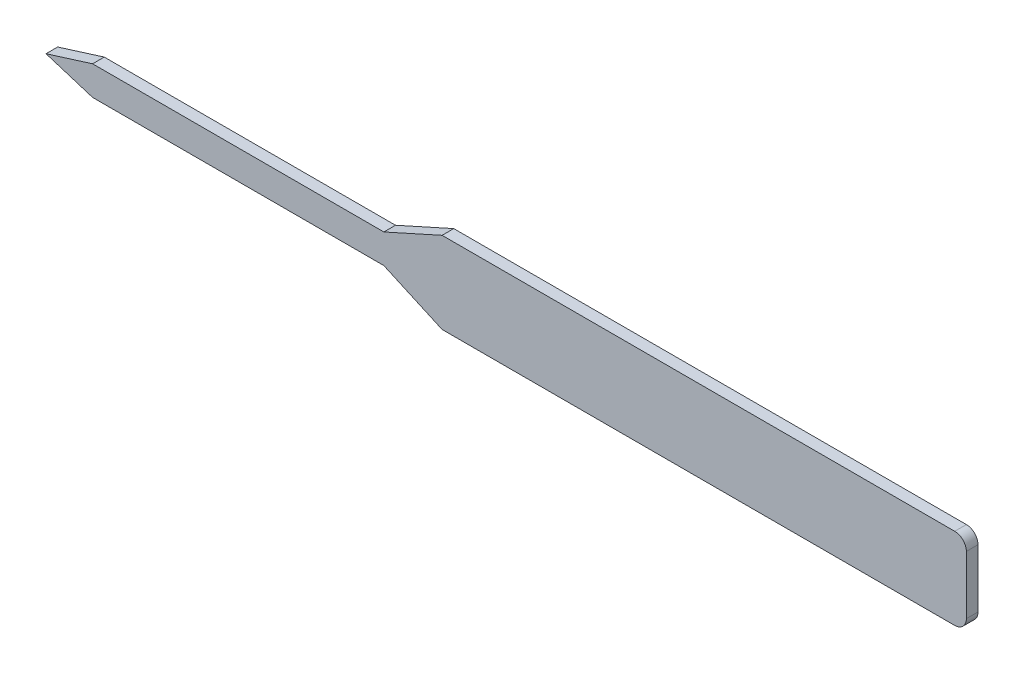
SolidWorks part; units mm, degrees
ref_plane "Front Plane" through (0, 0, 0) normal (0, 0, 1) x (1, 0, 0)
ref_plane "Top Plane" through (0, 0, 0) normal (0, 1, 0) x (1, 0, 0)
ref_plane "Right Plane" through (0, 0, 0) normal (1, 0, 0) x (0, 0, -1)
sketch "Sketch1" plane through (0, 0, 0) normal (0, 0, 1) x (1, 0, 0)
  line L0 (-45, 7) -> (-55, 2.5)
  line L1 (-45, 7) -> (45, 7)
  line L3 (-45, -7) -> (45, -7)
  line L4 (45, 7) -> (45, -7)
  line L5 (-45, 7) -> (45, -7) construction
  line L6 (-45, -7) -> (45, 7) construction
  line L7 (-55, -2.5) -> (-45, -7)
  line L8 (-105, 2.5) -> (-113, 0)
  line L9 (-105, 2.5) -> (-55, 2.5)
  line L11 (-105, -2.5) -> (-55, -2.5)
  line L13 (-105, 2.5) -> (-55, -2.5) construction
  line L14 (-105, -2.5) -> (-55, 2.5) construction
  line L15 (-113, 0) -> (-105, -2.5)
  point P0 (0, 0)
  point P6 (-80, 0)
  point P7 (0, 0)
  point P12 (-116.8459, 0.1547)
  point P13 (0, 0)
  point P14 (-118.9822, 0)
  dimension "D1" = 14
  dimension "D2" = 90
  dimension "D3" = 5
  dimension "D4" = 8
  dimension "D5" = 10
  dimension "D6" = 50
extrude "Boss-Extrude1" add sketch "Sketch1" along normal blind 2
fillet "Fillet1" radius 2 2 edges at (45, -7, 1) (45, 7, 1)
